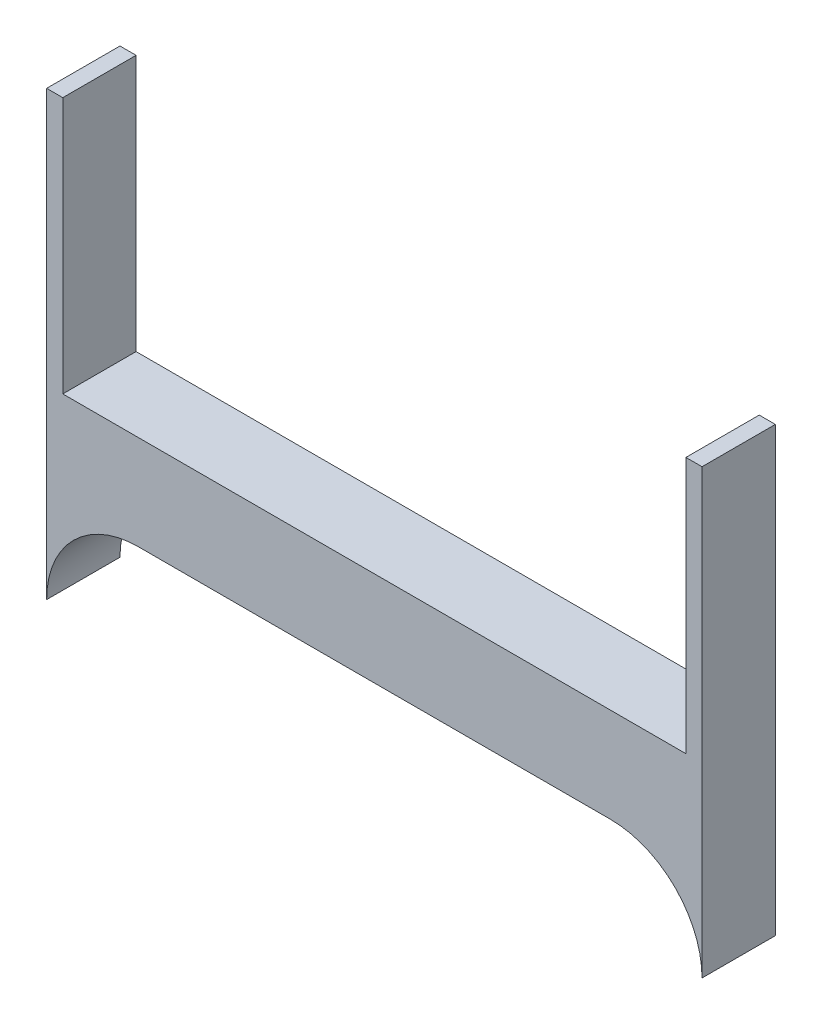
SolidWorks part; units mm, degrees
ref_plane "Front Plane" through (0, 0, 0) normal (0, 0, 1) x (1, 0, 0)
ref_plane "Top Plane" through (0, 0, 0) normal (0, 1, 0) x (1, 0, 0)
ref_plane "Right Plane" through (0, 0, 0) normal (1, 0, 0) x (0, 0, -1)
sketch "Sketch1" plane through (0, 0, 0) normal (0, 0, 1) x (1, 0, 0)
  line L3 (0, -6.04) -> (0, 0)
  line L4 (0, 0) -> (0.22, 0)
  line L5 (8.94, 0) -> (8.94, -6.04)
  line L9 (0.22, 0) -> (0.22, -3.5)
  line L10 (0.22, -3.5) -> (8.72, -3.5)
  line L11 (8.72, 0) -> (8.72, -3.5)
  line L12 (8.72, 0) -> (8.94, 0)
  line L13 (1.25, -4.79) -> (7.69, -4.79)
  arc A2 (8.94, -6.04) -> (7.69, -4.79) centre (7.69, -6.04) ccw
  arc A3 (1.25, -4.79) -> (0, -6.04) centre (1.25, -6.04) ccw
  point P3 (4.7657, -4.0942)
  point P4 (5.3746, -4.8597)
  dimension "D2" = 6.44
  dimension "D12" = 1.25
  dimension "D3" = 1.29
  dimension "D4" = 8.94
  dimension "D5" = 6.04
  dimension "D6" = 6.04
  dimension "D9" = 8.5
  dimension "D10" = 3.5
  dimension "D11" = 0.22
  dimension "D13" = 1.25
extrude "Boss-Extrude1" add sketch "Sketch1" along normal blind 1
